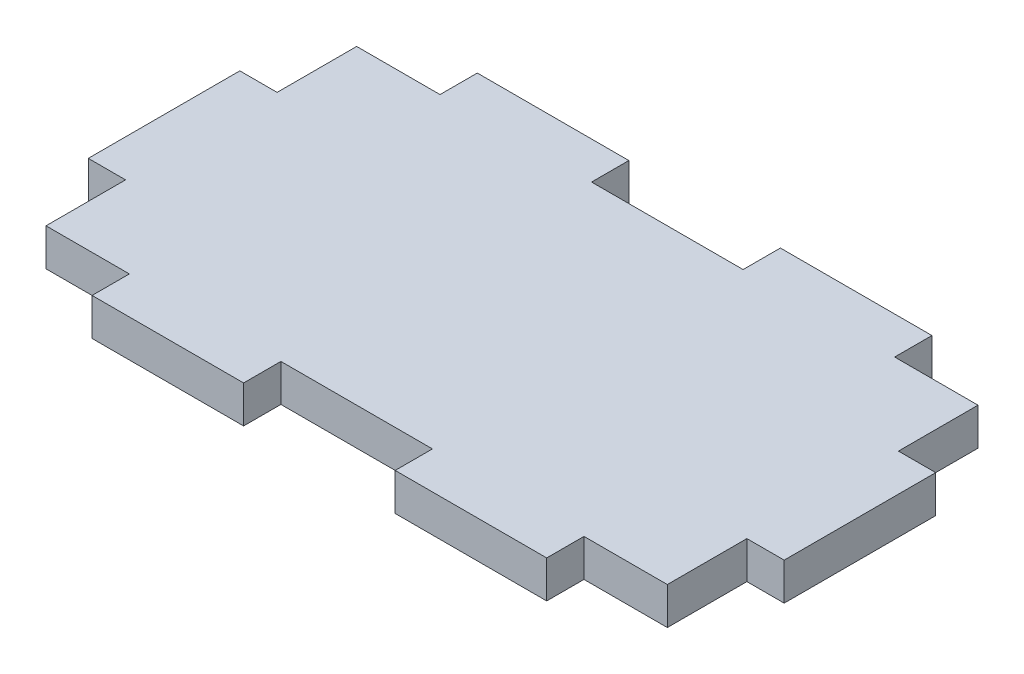
SolidWorks part; units mm, degrees
ref_plane "Front Plane" through (0, 0, 0) normal (0, 0, 1) x (1, 0, 0)
ref_plane "Top Plane" through (0, 0, 0) normal (0, 1, 0) x (1, 0, 0)
ref_plane "Right Plane" through (0, 0, 0) normal (1, 0, 0) x (0, 0, -1)
sketch "Sketch1" plane through (0, 0, 0) normal (0, 1, 0) x (1, 0, 0)
  line L0 (186, 59) -> (186, 46.195)
  line L1 (186, 46.195) -> (180, 46.195)
  line L2 (180, 46.195) -> (180, 21.805)
  line L3 (180, 21.805) -> (186, 21.805)
  line L4 (186, 21.805) -> (186, 9)
  line L5 (186, 9) -> (199.415, 9)
  line L6 (199.415, 9) -> (199.415, 3)
  line L7 (199.415, 3) -> (223.805, 3)
  line L8 (223.805, 3) -> (223.805, 9)
  line L9 (223.805, 9) -> (248.195, 9)
  line L10 (248.195, 9) -> (248.195, 3)
  line L11 (248.195, 3) -> (272.585, 3)
  line L12 (272.585, 3) -> (272.585, 9)
  line L13 (272.585, 9) -> (286, 9)
  line L14 (286, 9) -> (286, 21.805)
  line L15 (286, 21.805) -> (292, 21.805)
  line L16 (292, 21.805) -> (292, 46.195)
  line L17 (292, 46.195) -> (286, 46.195)
  line L18 (286, 46.195) -> (286, 59)
  line L19 (286, 59) -> (272.585, 59)
  line L20 (272.585, 59) -> (272.585, 65)
  line L21 (272.585, 65) -> (248.195, 65)
  line L22 (248.195, 65) -> (248.195, 59)
  line L23 (248.195, 59) -> (223.805, 59)
  line L24 (223.805, 59) -> (223.805, 65)
  line L25 (223.805, 65) -> (199.415, 65)
  line L26 (199.415, 65) -> (199.415, 59)
  line L27 (199.415, 59) -> (186, 59)
extrude "Boss-Extrude1" add sketch "Sketch1" along normal blind 6
